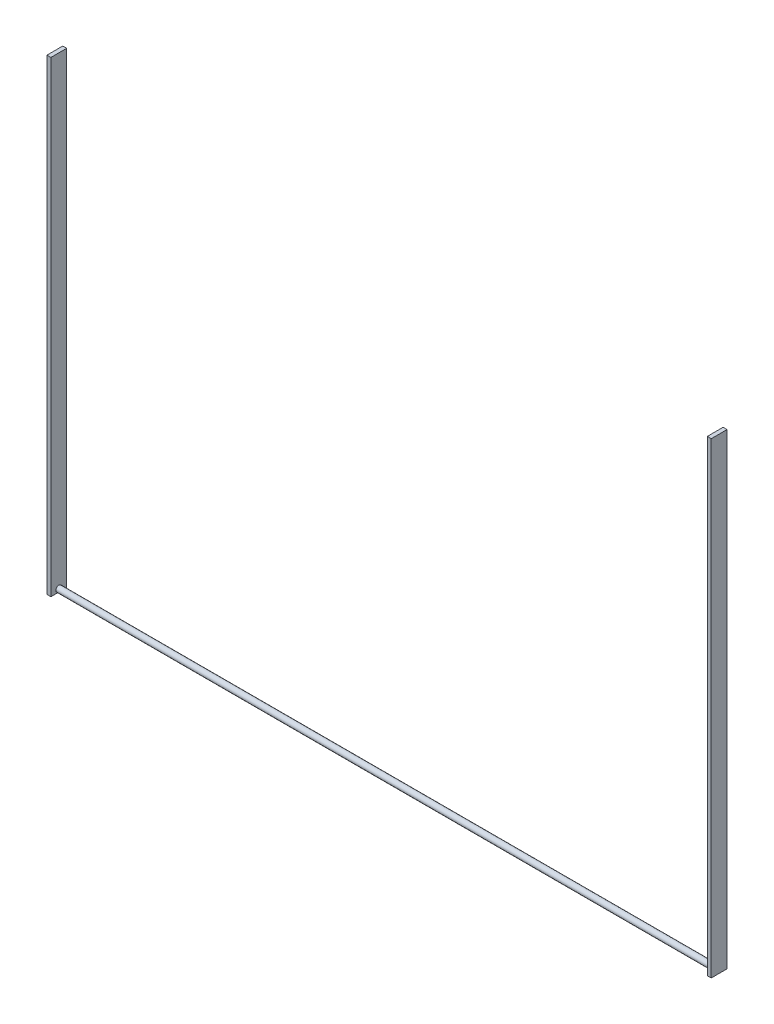
SolidWorks part; units mm, degrees
ref_plane "Alzado" through (0, 0, 0) normal (0, 0, 1) x (1, 0, 0)
ref_plane "Planta" through (0, 0, 0) normal (0, 1, 0) x (1, 0, 0)
ref_plane "Vista lateral" through (0, 0, 0) normal (1, 0, 0) x (0, 0, -1)
sketch "Croquis1" plane through (0, 0, 0) normal (0, 0, 1) x (1, 0, 0)
  line L0 (0, 0) -> (0, 750)
  line L1 (0, 750) -> (6.35, 750)
  line L2 (6.35, 750) -> (6.35, 0)
  line L3 (6.35, 0) -> (0, 0)
  line L4 (6.35, 0) -> (533.35, 0) construction
  line L5 (533.35, 0) -> (533.35, 846.7279) construction
  line L6 (1060.35, 0) -> (1066.7, 0)
  line L7 (1060.35, 750) -> (1060.35, 0)
  line L8 (1066.7, 750) -> (1060.35, 750)
  line L9 (1066.7, 0) -> (1066.7, 750)
  dimension "D1" = 6.35
  dimension "D2" = 750
  dimension "D3" = 527
extrude "Saliente-Extruir1" add sketch "Croquis1" along normal blind 25.4
sketch "Croquis2" plane through (6.35, 0, 0) normal (1, 0, 0) x (0, 0, -1)
  line L0 (-12.7, 0) -> (-12.7, 5) construction
  line L1 (-25.4, 0) -> (0, 0) construction
  circle A0 centre (-12.7, 5) radius 4.7625
  dimension "D2" = 9.525
  dimension "D1" = 5
extrude "Saliente-Extruir2" add sketch "Croquis2" along normal up to surface (1054 mm away) up to face at (1060.35, 375, 12.7)
